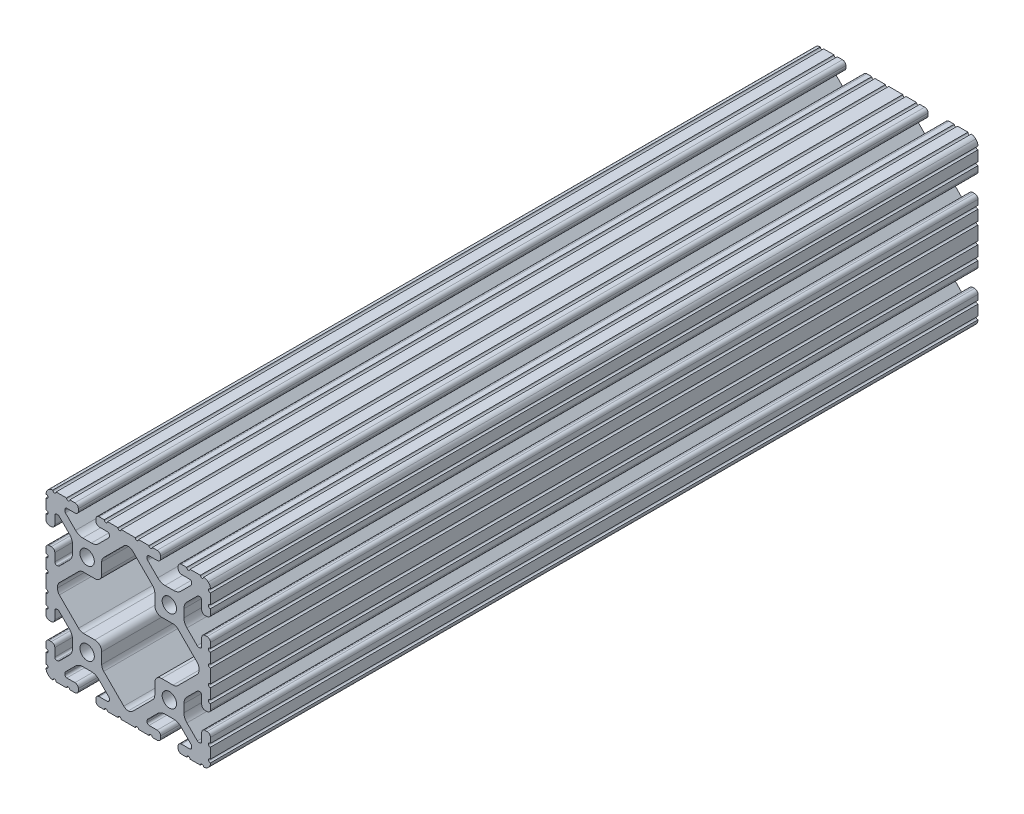
SolidWorks part; units mm, degrees
material "6061-T6 (SS)"
ref_plane "Front" through (0, 0, 0) normal (0, 0, 1) x (1, 0, 0)
ref_plane "Top" through (0, 0, 0) normal (0, 1, 0) x (1, 0, 0)
ref_plane "Right" through (0, 0, 0) normal (1, 0, 0) x (0, 0, -1)
ref_plane "Plane1" through (0, 0, -609.6) normal (0, 0, -1) x (-1, 0, 0)
sketch "Sketch1" plane through (0, 0, -609.6) normal (0, 0, -1) x (-1, 0, 0)
  line L0 (31.9021, -2.4756) -> (23.0141, -11.3637)
  line L1 (20.769, -12.2936) -> (15.4686, -12.2936)
  line L2 (12.2936, -15.4686) -> (12.2936, -20.5983)
  line L3 (11.3637, -22.8433) -> (2.0515, -32.1555)
  line L4 (-2.0515, -32.1555) -> (-11.3637, -22.8433)
  line L5 (-12.2936, -20.5983) -> (-12.2936, -15.4686)
  line L6 (-15.4686, -12.2936) -> (-20.769, -12.2936)
  line L7 (-23.0141, -11.3637) -> (-31.9021, -2.4756)
  line L8 (-31.9021, 2.4756) -> (-23.0141, 11.3637)
  line L9 (-20.769, 12.2936) -> (-15.4686, 12.2936)
  line L10 (-12.2936, 15.4686) -> (-12.2936, 20.5983)
  line L11 (-11.3637, 22.8433) -> (-2.0515, 32.1555)
  line L12 (2.0515, 32.1555) -> (11.3637, 22.8433)
  line L13 (12.2936, 20.5983) -> (12.2936, 15.4686)
  line L14 (15.4686, 12.2936) -> (20.769, 12.2936)
  line L15 (23.0141, 11.3637) -> (31.9021, 2.4756)
  line L16 (36.5252, -23.0554) -> (35.6108, -23.0554)
  line L17 (34.036, -24.6302) -> (34.036, -28.448)
  line L18 (33.147, -29.337) -> (32.6643, -29.337)
  line L19 (32.0357, -29.0766) -> (27.1976, -24.2385)
  line L20 (25.8064, -20.8799) -> (25.8064, -17.2201)
  line L21 (27.1976, -13.8615) -> (31.9489, -9.1101)
  line L22 (32.7869, -8.763) -> (33.0603, -8.763)
  line L23 (34.036, -9.7387) -> (34.036, -13.4698)
  line L24 (35.6108, -15.0446) -> (36.5252, -15.0446)
  line L25 (38.1, -13.4698) -> (38.1, -11.075)
  line L26 (38.1, -9.552) -> (38.1, -4.7238)
  line L27 (38.1, -3.2007) -> (38.1, 3.2007)
  line L28 (38.1, 4.7238) -> (38.1, 9.552)
  line L29 (38.1, 11.075) -> (38.1, 13.4698)
  line L30 (36.5252, 15.0446) -> (35.6108, 15.0446)
  line L31 (34.036, 13.4698) -> (34.036, 9.7387)
  line L32 (33.0603, 8.763) -> (32.7869, 8.763)
  line L33 (31.9489, 9.1101) -> (27.1976, 13.8615)
  line L34 (25.8064, 17.2201) -> (25.8064, 20.8799)
  line L35 (27.1976, 24.2385) -> (32.0357, 29.0766)
  line L36 (32.6643, 29.337) -> (33.147, 29.337)
  line L37 (34.036, 28.448) -> (34.036, 24.6302)
  line L38 (35.6108, 23.0554) -> (36.5252, 23.0554)
  line L39 (38.1, 24.6302) -> (38.1, 27.0238)
  line L40 (38.1, 28.5453) -> (38.1, 33.373)
  line L41 (33.4288, 38.1) -> (28.6011, 38.1)
  line L42 (27.0772, 38.1) -> (24.6888, 38.1)
  line L43 (23.114, 36.5252) -> (23.114, 35.6108)
  line L44 (24.6888, 34.036) -> (28.448, 34.036)
  line L45 (29.337, 33.147) -> (29.337, 32.7207)
  line L46 (29.1002, 31.8885) -> (24.4093, 27.1976)
  line L47 (21.0507, 25.8064) -> (17.0493, 25.8064)
  line L48 (13.6907, 27.1976) -> (9.0234, 31.8649)
  line L49 (8.763, 32.4935) -> (8.763, 33.147)
  line L50 (9.652, 34.036) -> (13.4112, 34.036)
  line L51 (14.986, 35.6108) -> (14.986, 36.5252)
  line L52 (13.4112, 38.1) -> (11.1289, 38.1)
  line L53 (9.6053, 38.1) -> (4.7773, 38.1)
  line L54 (3.2537, 38.1) -> (-3.2537, 38.1)
  line L55 (-4.7773, 38.1) -> (-9.6053, 38.1)
  line L56 (-11.1289, 38.1) -> (-13.4112, 38.1)
  line L57 (-14.986, 36.5252) -> (-14.986, 35.6108)
  line L58 (-13.4112, 34.036) -> (-9.652, 34.036)
  line L59 (-8.763, 33.147) -> (-8.763, 32.4935)
  line L60 (-9.0234, 31.8649) -> (-13.6907, 27.1976)
  line L61 (-17.0493, 25.8064) -> (-21.0507, 25.8064)
  line L62 (-24.4093, 27.1976) -> (-29.1002, 31.8885)
  line L63 (-29.337, 32.7207) -> (-29.337, 33.147)
  line L64 (-28.448, 34.036) -> (-24.6888, 34.036)
  line L65 (-23.114, 35.6108) -> (-23.114, 36.5252)
  line L66 (-24.6888, 38.1) -> (-27.0772, 38.1)
  line L67 (-28.6011, 38.1) -> (-33.4288, 38.1)
  line L68 (-38.1, 33.373) -> (-38.1, 28.5453)
  line L69 (-38.1, 27.0238) -> (-38.1, 24.6302)
  line L70 (-36.5252, 23.0554) -> (-35.6108, 23.0554)
  line L71 (-34.036, 24.6302) -> (-34.036, 28.448)
  line L72 (-33.147, 29.337) -> (-32.6643, 29.337)
  line L73 (-32.0357, 29.0766) -> (-27.1976, 24.2385)
  line L74 (-25.8064, 20.8799) -> (-25.8064, 17.2201)
  line L75 (-27.1976, 13.8615) -> (-31.9489, 9.1101)
  line L76 (-32.7869, 8.763) -> (-33.0603, 8.763)
  line L77 (-34.036, 9.7387) -> (-34.036, 13.4698)
  line L78 (-35.6108, 15.0446) -> (-36.5252, 15.0446)
  line L79 (-38.1, 13.4698) -> (-38.1, 11.075)
  line L80 (-38.1, 9.552) -> (-38.1, 4.7238)
  line L81 (-38.1, 3.2007) -> (-38.1, -3.2007)
  line L82 (-38.1, -4.7238) -> (-38.1, -9.552)
  line L83 (-38.1, -11.075) -> (-38.1, -13.4698)
  line L84 (-36.5252, -15.0446) -> (-35.6108, -15.0446)
  line L85 (-34.036, -13.4698) -> (-34.036, -9.7387)
  line L86 (-33.0603, -8.763) -> (-32.7869, -8.763)
  line L87 (-31.9489, -9.1101) -> (-27.1976, -13.8615)
  line L88 (-25.8064, -17.2201) -> (-25.8064, -20.8799)
  line L89 (-27.1976, -24.2385) -> (-32.0357, -29.0766)
  line L90 (-32.6643, -29.337) -> (-33.147, -29.337)
  line L91 (-34.036, -28.448) -> (-34.036, -24.6302)
  line L92 (-35.6108, -23.0554) -> (-36.5252, -23.0554)
  line L93 (-38.1, -24.6302) -> (-38.1, -27.0238)
  line L94 (-38.1, -28.5453) -> (-38.1, -33.373)
  line L95 (-33.4288, -38.1) -> (-28.6011, -38.1)
  line L96 (-27.0772, -38.1) -> (-24.6888, -38.1)
  line L97 (-23.114, -36.5252) -> (-23.114, -35.6108)
  line L98 (-24.6888, -34.036) -> (-28.448, -34.036)
  line L99 (-29.337, -33.147) -> (-29.337, -32.7207)
  line L100 (-29.1002, -31.8885) -> (-24.4093, -27.1976)
  line L101 (-21.0507, -25.8064) -> (-17.0493, -25.8064)
  line L102 (-13.6907, -27.1976) -> (-9.0234, -31.8649)
  line L103 (-8.763, -32.4935) -> (-8.763, -33.147)
  line L104 (-9.652, -34.036) -> (-13.4112, -34.036)
  line L105 (-14.986, -35.6108) -> (-14.986, -36.5252)
  line L106 (-13.4112, -38.1) -> (-11.1289, -38.1)
  line L107 (-9.6053, -38.1) -> (-4.7773, -38.1)
  line L108 (-3.2537, -38.1) -> (3.2537, -38.1)
  line L109 (4.7773, -38.1) -> (9.6053, -38.1)
  line L110 (11.1289, -38.1) -> (13.4112, -38.1)
  line L111 (14.986, -36.5252) -> (14.986, -35.6108)
  line L112 (13.4112, -34.036) -> (9.652, -34.036)
  line L113 (8.763, -33.147) -> (8.763, -32.4935)
  line L114 (9.0234, -31.8649) -> (13.6907, -27.1976)
  line L115 (17.0493, -25.8064) -> (21.0507, -25.8064)
  line L116 (24.4093, -27.1976) -> (29.1002, -31.8885)
  line L117 (29.337, -32.7207) -> (29.337, -33.147)
  line L118 (28.448, -34.036) -> (24.6888, -34.036)
  line L119 (23.114, -35.6108) -> (23.114, -36.5252)
  line L120 (24.6888, -38.1) -> (27.0772, -38.1)
  line L121 (28.6011, -38.1) -> (33.4288, -38.1)
  line L122 (38.1, -33.373) -> (38.1, -28.5453)
  line L123 (38.1, -27.0238) -> (38.1, -24.6302)
  arc A0 (31.9021, 2.4756) -> (32.7287, 0) centre (29.8367, 0.4102) cw
  arc A1 (32.7287, 0) -> (31.9021, -2.4756) centre (29.8367, -0.4102) cw
  arc A2 (23.0141, -11.3637) -> (20.769, -12.2936) centre (20.769, -9.1186) cw
  arc A3 (15.4686, -12.2936) -> (12.2936, -15.4686) centre (15.4686, -15.4686) ccw
  arc A4 (12.2936, -20.5983) -> (11.3637, -22.8433) centre (9.1186, -20.5983) cw
  arc A5 (2.0515, -32.1555) -> (0, -33.011) centre (-0.0139, -30.09) cw
  arc A6 (0, -33.011) -> (-2.0515, -32.1555) centre (0.0139, -30.09) cw
  arc A7 (-11.3637, -22.8433) -> (-12.2936, -20.5983) centre (-9.1186, -20.5983) cw
  arc A8 (-12.2936, -15.4686) -> (-15.4686, -12.2936) centre (-15.4686, -15.4686) ccw
  arc A9 (-20.769, -12.2936) -> (-23.0141, -11.3637) centre (-20.769, -9.1186) cw
  arc A10 (-31.9021, -2.4756) -> (-32.7287, 0) centre (-29.8367, -0.4102) cw
  arc A11 (-32.7287, 0) -> (-31.9021, 2.4756) centre (-29.8367, 0.4102) cw
  arc A12 (-23.0141, 11.3637) -> (-20.769, 12.2936) centre (-20.769, 9.1186) cw
  arc A13 (-15.4686, 12.2936) -> (-12.2936, 15.4686) centre (-15.4686, 15.4686) ccw
  arc A14 (-12.2936, 20.5983) -> (-11.3637, 22.8433) centre (-9.1186, 20.5983) cw
  arc A15 (-2.0515, 32.1555) -> (0, 33.011) centre (0.0139, 30.09) cw
  arc A16 (0, 33.011) -> (2.0515, 32.1555) centre (-0.0139, 30.09) cw
  arc A17 (11.3637, 22.8433) -> (12.2936, 20.5983) centre (9.1186, 20.5983) cw
  arc A18 (12.2936, 15.4686) -> (15.4686, 12.2936) centre (15.4686, 15.4686) ccw
  arc A19 (20.769, 12.2936) -> (23.0141, 11.3637) centre (20.769, 9.1186) cw
  circle A20 centre (19.05, -19.05) radius 3.3274
  circle A21 centre (19.05, 19.05) radius 3.3274
  circle A22 centre (-19.05, 19.05) radius 3.3274
  circle A23 centre (-19.05, -19.05) radius 3.3274
  arc A24 (38.1, -24.6302) -> (36.5252, -23.0554) centre (36.5252, -24.6302) ccw
  arc A25 (35.6108, -23.0554) -> (34.036, -24.6302) centre (35.6108, -24.6302) ccw
  arc A26 (34.036, -28.448) -> (33.147, -29.337) centre (33.147, -28.448) cw
  arc A27 (32.6643, -29.337) -> (32.0357, -29.0766) centre (32.6643, -28.448) cw
  arc A28 (27.1976, -24.2385) -> (25.8064, -20.8799) centre (30.5562, -20.8799) cw
  arc A29 (25.8064, -17.2201) -> (27.1976, -13.8615) centre (30.5562, -17.2201) cw
  arc A30 (31.9489, -9.1101) -> (32.7869, -8.763) centre (32.7869, -9.9481) cw
  arc A31 (33.0603, -8.763) -> (34.036, -9.7387) centre (33.0603, -9.7387) cw
  arc A32 (34.036, -13.4698) -> (35.6108, -15.0446) centre (35.6108, -13.4698) ccw
  arc A33 (36.5252, -15.0446) -> (38.1, -13.4698) centre (36.5252, -13.4698) ccw
  arc A34 (38.1, -11.075) -> (38.1, -9.552) centre (37.9035, -10.3135) cw
  arc A35 (38.1, -4.7238) -> (38.1, -3.2007) centre (37.9035, -3.9622) cw
  arc A36 (38.1, 3.2007) -> (38.1, 4.7238) centre (37.9035, 3.9622) cw
  arc A37 (38.1, 9.552) -> (38.1, 11.075) centre (37.9035, 10.3135) cw
  arc A38 (38.1, 13.4698) -> (36.5252, 15.0446) centre (36.5252, 13.4698) ccw
  arc A39 (35.6108, 15.0446) -> (34.036, 13.4698) centre (35.6108, 13.4698) ccw
  arc A40 (34.036, 9.7387) -> (33.0603, 8.763) centre (33.0603, 9.7387) cw
  arc A41 (32.7869, 8.763) -> (31.9489, 9.1101) centre (32.7869, 9.9481) cw
  arc A42 (27.1976, 13.8615) -> (25.8064, 17.2201) centre (30.5562, 17.2201) cw
  arc A43 (25.8064, 20.8799) -> (27.1976, 24.2385) centre (30.5562, 20.8799) cw
  arc A44 (32.0357, 29.0766) -> (32.6643, 29.337) centre (32.6643, 28.448) cw
  arc A45 (33.147, 29.337) -> (34.036, 28.448) centre (33.147, 28.448) cw
  arc A46 (34.036, 24.6302) -> (35.6108, 23.0554) centre (35.6108, 24.6302) ccw
  arc A47 (36.5252, 23.0554) -> (38.1, 24.6302) centre (36.5252, 24.6302) ccw
  arc A48 (38.1, 27.0238) -> (38.1, 28.5453) centre (37.9035, 27.7845) cw
  arc A49 (38.1, 33.373) -> (38.1, 34.8455) centre (37.9035, 34.1092) cw
  arc A50 (38.1, 34.8455) -> (37.0861, 37.1826) centre (34.925, 34.8566) ccw
  arc A51 (37.0861, 37.1826) -> (34.9527, 38.1) centre (34.8521, 34.9266) ccw
  arc A52 (34.9527, 38.1) -> (33.4288, 38.1) centre (34.1907, 38.0824) cw
  arc A53 (28.6011, 38.1) -> (27.0772, 38.1) centre (27.8392, 38.0824) cw
  arc A54 (24.6888, 38.1) -> (23.114, 36.5252) centre (24.6888, 36.5252) ccw
  arc A55 (23.114, 35.6108) -> (24.6888, 34.036) centre (24.6888, 35.6108) ccw
  arc A56 (28.448, 34.036) -> (29.337, 33.147) centre (28.448, 33.147) cw
  arc A57 (29.337, 32.7207) -> (29.1002, 31.8885) centre (28.4716, 32.5172) cw
  arc A58 (24.4093, 27.1976) -> (21.0507, 25.8064) centre (21.0507, 30.5562) cw
  arc A59 (17.0493, 25.8064) -> (13.6907, 27.1976) centre (17.0493, 30.5562) cw
  arc A60 (9.0234, 31.8649) -> (8.763, 32.4935) centre (9.652, 32.4935) cw
  arc A61 (8.763, 33.147) -> (9.652, 34.036) centre (9.652, 33.147) cw
  arc A62 (13.4112, 34.036) -> (14.986, 35.6108) centre (13.4112, 35.6108) ccw
  arc A63 (14.986, 36.5252) -> (13.4112, 38.1) centre (13.4112, 36.5252) ccw
  arc A64 (11.1289, 38.1) -> (9.6053, 38.1) centre (10.3671, 38.0824) cw
  arc A65 (4.7773, 38.1) -> (3.2537, 38.1) centre (4.0155, 38.0824) cw
  arc A66 (-3.2537, 38.1) -> (-4.7773, 38.1) centre (-4.0155, 38.0824) cw
  arc A67 (-9.6053, 38.1) -> (-11.1289, 38.1) centre (-10.3671, 38.0824) cw
  arc A68 (-13.4112, 38.1) -> (-14.986, 36.5252) centre (-13.4112, 36.5252) ccw
  arc A69 (-14.986, 35.6108) -> (-13.4112, 34.036) centre (-13.4112, 35.6108) ccw
  arc A70 (-9.652, 34.036) -> (-8.763, 33.147) centre (-9.652, 33.147) cw
  arc A71 (-8.763, 32.4935) -> (-9.0234, 31.8649) centre (-9.652, 32.4935) cw
  arc A72 (-13.6907, 27.1976) -> (-17.0493, 25.8064) centre (-17.0493, 30.5562) cw
  arc A73 (-21.0507, 25.8064) -> (-24.4093, 27.1976) centre (-21.0507, 30.5562) cw
  arc A74 (-29.1002, 31.8885) -> (-29.337, 32.7207) centre (-28.4716, 32.5172) cw
  arc A75 (-29.337, 33.147) -> (-28.448, 34.036) centre (-28.448, 33.147) cw
  arc A76 (-24.6888, 34.036) -> (-23.114, 35.6108) centre (-24.6888, 35.6108) ccw
  arc A77 (-23.114, 36.5252) -> (-24.6888, 38.1) centre (-24.6888, 36.5252) ccw
  arc A78 (-27.0772, 38.1) -> (-28.6011, 38.1) centre (-27.8392, 38.0824) cw
  arc A79 (-33.4288, 38.1) -> (-34.9527, 38.1) centre (-34.1907, 38.0824) cw
  arc A80 (-34.9527, 38.1) -> (-37.0861, 37.1826) centre (-34.8521, 34.9266) ccw
  arc A81 (-37.0861, 37.1826) -> (-38.1, 34.8455) centre (-34.925, 34.8566) ccw
  arc A82 (-38.1, 34.8455) -> (-38.1, 33.373) centre (-37.9035, 34.1092) cw
  arc A83 (-38.1, 28.5453) -> (-38.1, 27.0238) centre (-37.9035, 27.7845) cw
  arc A84 (-38.1, 24.6302) -> (-36.5252, 23.0554) centre (-36.5252, 24.6302) ccw
  arc A85 (-35.6108, 23.0554) -> (-34.036, 24.6302) centre (-35.6108, 24.6302) ccw
  arc A86 (-34.036, 28.448) -> (-33.147, 29.337) centre (-33.147, 28.448) cw
  arc A87 (-32.6643, 29.337) -> (-32.0357, 29.0766) centre (-32.6643, 28.448) cw
  arc A88 (-27.1976, 24.2385) -> (-25.8064, 20.8799) centre (-30.5562, 20.8799) cw
  arc A89 (-25.8064, 17.2201) -> (-27.1976, 13.8615) centre (-30.5562, 17.2201) cw
  arc A90 (-31.9489, 9.1101) -> (-32.7869, 8.763) centre (-32.7869, 9.9481) cw
  arc A91 (-33.0603, 8.763) -> (-34.036, 9.7387) centre (-33.0603, 9.7387) cw
  arc A92 (-34.036, 13.4698) -> (-35.6108, 15.0446) centre (-35.6108, 13.4698) ccw
  arc A93 (-36.5252, 15.0446) -> (-38.1, 13.4698) centre (-36.5252, 13.4698) ccw
  arc A94 (-38.1, 11.075) -> (-38.1, 9.552) centre (-37.9035, 10.3135) cw
  arc A95 (-38.1, 4.7238) -> (-38.1, 3.2007) centre (-37.9035, 3.9622) cw
  arc A96 (-38.1, -3.2007) -> (-38.1, -4.7238) centre (-37.9035, -3.9622) cw
  arc A97 (-38.1, -9.552) -> (-38.1, -11.075) centre (-37.9035, -10.3135) cw
  arc A98 (-38.1, -13.4698) -> (-36.5252, -15.0446) centre (-36.5252, -13.4698) ccw
  arc A99 (-35.6108, -15.0446) -> (-34.036, -13.4698) centre (-35.6108, -13.4698) ccw
  arc A100 (-34.036, -9.7387) -> (-33.0603, -8.763) centre (-33.0603, -9.7387) cw
  arc A101 (-32.7869, -8.763) -> (-31.9489, -9.1101) centre (-32.7869, -9.9481) cw
  arc A102 (-27.1976, -13.8615) -> (-25.8064, -17.2201) centre (-30.5562, -17.2201) cw
  arc A103 (-25.8064, -20.8799) -> (-27.1976, -24.2385) centre (-30.5562, -20.8799) cw
  arc A104 (-32.0357, -29.0766) -> (-32.6643, -29.337) centre (-32.6643, -28.448) cw
  arc A105 (-33.147, -29.337) -> (-34.036, -28.448) centre (-33.147, -28.448) cw
  arc A106 (-34.036, -24.6302) -> (-35.6108, -23.0554) centre (-35.6108, -24.6302) ccw
  arc A107 (-36.5252, -23.0554) -> (-38.1, -24.6302) centre (-36.5252, -24.6302) ccw
  arc A108 (-38.1, -27.0238) -> (-38.1, -28.5453) centre (-37.9035, -27.7845) cw
  arc A109 (-38.1, -33.373) -> (-38.1, -34.8455) centre (-37.9035, -34.1092) cw
  arc A110 (-38.1, -34.8455) -> (-37.0861, -37.1826) centre (-34.925, -34.8566) ccw
  arc A111 (-37.0861, -37.1826) -> (-34.9527, -38.1) centre (-34.8521, -34.9266) ccw
  arc A112 (-34.9527, -38.1) -> (-33.4288, -38.1) centre (-34.1907, -38.0824) cw
  arc A113 (-28.6011, -38.1) -> (-27.0772, -38.1) centre (-27.8392, -38.0824) cw
  arc A114 (-24.6888, -38.1) -> (-23.114, -36.5252) centre (-24.6888, -36.5252) ccw
  arc A115 (-23.114, -35.6108) -> (-24.6888, -34.036) centre (-24.6888, -35.6108) ccw
  arc A116 (-28.448, -34.036) -> (-29.337, -33.147) centre (-28.448, -33.147) cw
  arc A117 (-29.337, -32.7207) -> (-29.1002, -31.8885) centre (-28.4716, -32.5172) cw
  arc A118 (-24.4093, -27.1976) -> (-21.0507, -25.8064) centre (-21.0507, -30.5562) cw
  arc A119 (-17.0493, -25.8064) -> (-13.6907, -27.1976) centre (-17.0493, -30.5562) cw
  arc A120 (-9.0234, -31.8649) -> (-8.763, -32.4935) centre (-9.652, -32.4935) cw
  arc A121 (-8.763, -33.147) -> (-9.652, -34.036) centre (-9.652, -33.147) cw
  arc A122 (-13.4112, -34.036) -> (-14.986, -35.6108) centre (-13.4112, -35.6108) ccw
  arc A123 (-14.986, -36.5252) -> (-13.4112, -38.1) centre (-13.4112, -36.5252) ccw
  arc A124 (-11.1289, -38.1) -> (-9.6053, -38.1) centre (-10.3671, -38.0824) cw
  arc A125 (-4.7773, -38.1) -> (-3.2537, -38.1) centre (-4.0155, -38.0824) cw
  arc A126 (3.2537, -38.1) -> (4.7773, -38.1) centre (4.0155, -38.0824) cw
  arc A127 (9.6053, -38.1) -> (11.1289, -38.1) centre (10.3671, -38.0824) cw
  arc A128 (13.4112, -38.1) -> (14.986, -36.5252) centre (13.4112, -36.5252) ccw
  arc A129 (14.986, -35.6108) -> (13.4112, -34.036) centre (13.4112, -35.6108) ccw
  arc A130 (9.652, -34.036) -> (8.763, -33.147) centre (9.652, -33.147) cw
  arc A131 (8.763, -32.4935) -> (9.0234, -31.8649) centre (9.652, -32.4935) cw
  arc A132 (13.6907, -27.1976) -> (17.0493, -25.8064) centre (17.0493, -30.5562) cw
  arc A133 (21.0507, -25.8064) -> (24.4093, -27.1976) centre (21.0507, -30.5562) cw
  arc A134 (29.1002, -31.8885) -> (29.337, -32.7207) centre (28.4716, -32.5172) cw
  arc A135 (29.337, -33.147) -> (28.448, -34.036) centre (28.448, -33.147) cw
  arc A136 (24.6888, -34.036) -> (23.114, -35.6108) centre (24.6888, -35.6108) ccw
  arc A137 (23.114, -36.5252) -> (24.6888, -38.1) centre (24.6888, -36.5252) ccw
  arc A138 (27.0772, -38.1) -> (28.6011, -38.1) centre (27.8392, -38.0824) cw
  arc A139 (33.4288, -38.1) -> (34.9527, -38.1) centre (34.1907, -38.0824) cw
  arc A140 (34.9527, -38.1) -> (37.0861, -37.1826) centre (34.8521, -34.9266) ccw
  arc A141 (37.0861, -37.1826) -> (38.1, -34.8455) centre (34.925, -34.8566) ccw
  arc A142 (38.1, -34.8455) -> (38.1, -33.373) centre (37.9035, -34.1092) cw
  arc A143 (38.1, -28.5453) -> (38.1, -27.0238) centre (37.9035, -27.7845) cw
extrude "Boss-Extrude1" add sketch "Sketch1" against normal blind 355.6
